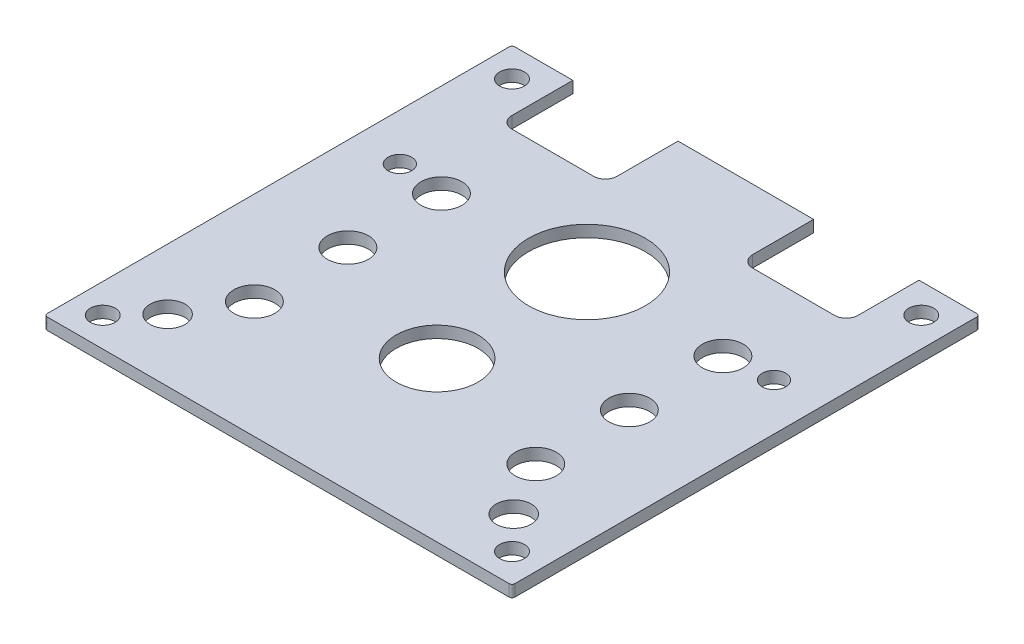
SolidWorks part; units mm, degrees
material "6061 Alloy"
ref_plane "Front Plane" through (0, 0, 0) normal (0, 0, 1) x (1, 0, 0)
ref_plane "Top Plane" through (0, 0, 0) normal (0, 1, 0) x (1, 0, 0)
ref_plane "Right Plane" through (0, 0, 0) normal (1, 0, 0) x (0, 0, -1)
sketch "Sketch1" plane through (0, 0, 0) normal (0, 1, 0) x (1, 0, 0)
  line L0 (-49.8269, 78.3102) -> (-49.8269, -48.6898)
  line L1 (-49.8269, -48.6898) -> (77.1731, -48.6898)
  line L2 (77.1731, -48.6898) -> (77.1731, 78.3102)
  line L3 (77.1731, 78.3102) -> (-49.8269, 78.3102)
extrude "Boss-Extrude1" add sketch "Sketch1" against normal blind 3.175
hole_wizard "M20 Clearance Hole1" positions "Sketch3" profile "Sketch2" hole size "M20" standard "Ansi Metric"
sketch "Sketch3" plane through (0, -3.175, 0) normal (0, -1, 0) x (1, 0, 0)
  point P0 (13.6731, 5.5352)
sketch "Sketch2" plane through (13.6731, -3.175, 5.5352) normal (1, 0, 0) x (0, 0, -1)
  line L0 (0, 0) -> (0, 3.175)
  line L1 (0, 3.175) -> (11.1125, 3.175)
  line L2 (11.1125, 3.175) -> (11.1125, 0)
  line L5 (11.1125, 0) -> (0, 0)
  line L11 (0, -6.35) -> (0, 107.95) construction
  dimension "Thru Hole Dia." = 22.225
  dimension "Thru Hole Depth" = 3.175
hole_wizard "M6 Clearance Hole1" positions "Sketch5" profile "Sketch4" hole size "M6" standard "Ansi Metric"
sketch "Sketch5" plane through (0, -3.175, 0) normal (0, -1, 0) x (1, 0, 0)
  point P0 (-41.8894, -70.3727)
  point P1 (69.2356, 40.7523)
  point P2 (69.2356, -70.3727)
  point P3 (-41.8894, 40.7523)
sketch "Sketch4" plane through (-41.8894, -3.175, -70.3727) normal (1, 0, 0) x (0, 0, -1)
  line L0 (0, 0) -> (0, 3.175)
  line L1 (0, 3.175) -> (3.3528, 3.175)
  line L2 (3.3528, 3.175) -> (3.3528, 0)
  line L5 (3.3528, 0) -> (0, 0)
  line L11 (0, -6.35) -> (0, 107.95) construction
  dimension "Thru Hole Dia." = 6.7056
  dimension "Thru Hole Depth" = 3.175
hole_wizard "Hole1" positions "Sketch7" profile "Sketch6" legacy end condition through all
sketch "Sketch7" plane through (0, -3.175, 0) normal (0, -1, 0) x (1, 0, 0)
  point P0 (13.6731, -35.1556)
sketch "Sketch6" plane through (13.6731, -3.175, -35.1556) normal (1, 0, 0) x (0, 0, -1)
  line L0 (0, 0) -> (0, 3.175)
  line L1 (0, 3.175) -> (15.875, 3.175)
  line L2 (15.875, 3.175) -> (15.875, 0)
  line L3 (15.875, 0) -> (0, 0)
  line L4 (0, 110) -> (0, -10) construction
  dimension "Diameter" = 31.75
  dimension "Depth" = 3.175
hole_wizard "M10 Clearance Hole1" positions "Sketch9" profile "Sketch8" hole size "M10" standard "Ansi Metric"
sketch "Sketch9" plane through (0, -3.175, 0) normal (0, -1, 0) x (1, 0, 0)
  point P0 (-24.5351, -33.8602)
  point P1 (51.8813, 16.9398)
  point P2 (-24.5351, -8.4602)
  point P3 (-24.5351, 16.9398)
  point P4 (51.8813, -33.8602)
  point P5 (51.8813, -8.4602)
sketch "Sketch8" plane through (-24.5351, -3.175, -33.8602) normal (1, 0, 0) x (0, 0, -1)
  line L0 (0, 0) -> (0, 3.175)
  line L1 (0, 3.175) -> (5.5626, 3.175)
  line L2 (5.5626, 3.175) -> (5.5626, 0)
  line L5 (5.5626, 0) -> (0, 0)
  line L11 (0, -6.35) -> (0, 107.95) construction
  dimension "Thru Hole Dia." = 11.1252
  dimension "Thru Hole Depth" = 3.175
fillet "Fillet1" radius 0.7937 4 edges at (77.1731, -1.5875, -78.3102) (77.1731, -1.5875, 48.6898) (-49.8269, -1.5875, -78.3102) (-49.8269, -1.5875, 48.6898)
hole_wizard "M6 Clearance Hole2" positions "Sketch11" profile "Sketch10" hole size "M6" standard "ISO" end condition up to next
sketch "Sketch11" plane through (0, 0, 0) normal (0, 1, 0) x (-1, 0, 0)
  line L0 (-13.6731, -5.5773) -> (-13.6731, -19.2806) construction
  line L2 (-77.1731, 47.896) -> (-77.1731, -77.5165) construction
  circle A0 centre (-13.6731, 5.5352) radius 11.1125 construction
  circle A1 centre (-13.6731, -35.1556) radius 15.875 construction
  circle A3 centre (-13.6731, -35.1556) radius 15.875
  point P0 (-64.4731, -35.1556)
  point P1 (37.1269, -35.1556)
  dimension "D1" = 12.7
sketch "Sketch10" plane through (64.4731, 0, -35.1556) normal (1, 0, 0) x (0, 0, 1)
  line L0 (0, 0) -> (0, 3.175)
  line L1 (0, 3.175) -> (3.2, 3.175)
  line L2 (3.2, 3.175) -> (3.2, 0)
  line L5 (3.2, 0) -> (0, 0)
  line L11 (0, -6.35) -> (0, 107.95) construction
  dimension "Thru Hole Dia." = 6.4
  dimension "Thru Hole Depth" = 3.175
extrude "Cut-Extrude1" cut sketch "Sketch12" against normal through all
sketch "Sketch12" plane through (0, -3.175, 0) normal (0, -1, 0) x (1, 0, 0)
  line L0 (-33.3169, -78.3102) -> (-33.3169, -61.7463)
  line L2 (-30.1419, -58.5713) -> (-7.9169, -58.5713)
  line L3 (-4.7419, -61.7463) -> (-4.7419, -78.3102)
  line L4 (-4.7419, -78.3102) -> (-33.3169, -78.3102)
  line L5 (68.5276, -78.3102) -> (68.5276, -56.4455) construction
  line L6 (32.0754, -78.3102) -> (32.0754, -61.7463)
  line L8 (35.2504, -58.5713) -> (57.5008, -58.5713)
  line L9 (60.6758, -61.7463) -> (60.6758, -78.3102)
  line L10 (60.6758, -78.3102) -> (32.0754, -78.3102)
  arc A0 (-7.9169, -58.5713) -> (-4.7419, -61.7463) centre (-7.9169, -61.7463) cw
  arc A1 (-33.3169, -61.7463) -> (-30.1419, -58.5713) centre (-30.1419, -61.7463) cw
  arc A2 (57.5008, -58.5713) -> (60.6758, -61.7463) centre (57.5008, -61.7463) cw
  arc A3 (32.0754, -61.7463) -> (35.2504, -58.5713) centre (35.2504, -61.7463) cw
  point P20 (-4.7419, -58.5713)
  point P23 (-33.3169, -58.5713)
  point P26 (170.372, -58.5713)
  point P29 (141.797, -58.5713)
hole_wizard "3/8 (0.375) Diameter Hole1" positions "Sketch14" profile "Sketch13" hole size "3/8" standard "Ansi Inch" end condition up to next
sketch "Sketch14" plane through (0, -3.175, 0) normal (0, -1, 0) x (1, 0, 0)
  circle A0 centre (60.6631, 31.7175) radius 3.2 construction
  point P0 (60.6631, 31.7175)
  point P1 (-33.3169, 31.7175)
sketch "Sketch13" plane through (60.6631, -3.175, 31.7175) normal (1, 0, 0) x (0, 0, -1)
  line L0 (0, 0) -> (0, 3.175)
  line L1 (0, 3.175) -> (4.7625, 3.175)
  line L2 (4.7625, 3.175) -> (4.7625, 0)
  line L5 (4.7625, 0) -> (0, 0)
  line L11 (0, -6.35) -> (0, 107.95) construction
  dimension "Thru Hole Dia." = 9.525
  dimension "Thru Hole Depth" = 3.175
